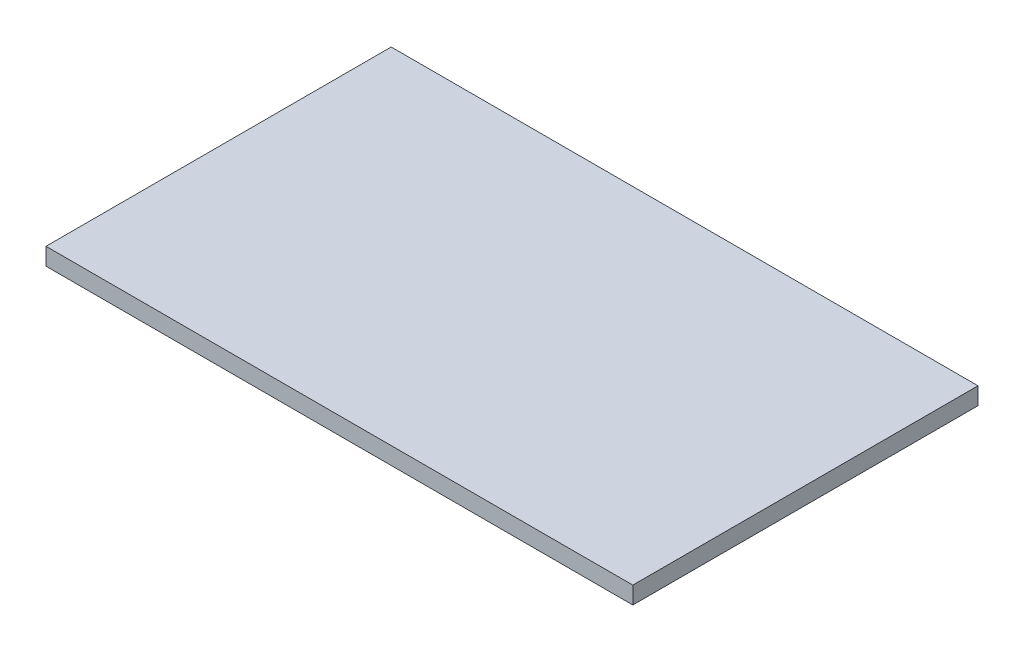
SolidWorks part; units mm, degrees
ref_plane "Front Plane" through (0, 0, 0) normal (0, 0, 1) x (1, 0, 0)
ref_plane "Top Plane" through (0, 0, 0) normal (0, 1, 0) x (1, 0, 0)
ref_plane "Right Plane" through (0, 0, 0) normal (1, 0, 0) x (0, 0, -1)
sketch "Sketch1" plane through (0, 0, 0) normal (0, 1, 0) x (1, 0, 0)
  line L0 (0, 0) -> (0, 254)
  line L1 (0, 254) -> (431.8, 254)
  line L2 (431.8, 254) -> (431.8, 0)
  line L3 (431.8, 0) -> (0, 0)
  dimension "D1" = 254
  dimension "D2" = 431.8
extrude "Boss-Extrude1" add sketch "Sketch1" along normal blind 12.7 contours L3 L0 L1 L2
sketch "Sketch2" plane through (0, 12.7, 0) normal (0, 1, 0) x (1, 0, 0)
  line L0 (0, 228.6) -> (431.8, 228.6)
  line L1 (0, 0) -> (0, 254) construction
  line L2 (431.8, 254) -> (431.8, 0) construction
  line L3 (0, 254) -> (431.8, 254) construction
  line L4 (0, 203.2) -> (431.8, 203.2)
  line L5 (0, 177.8) -> (431.8, 177.8)
  line L6 (0, 152.4) -> (431.8, 152.4)
  line L7 (0, 127) -> (431.8, 127)
  line L8 (0, 101.6) -> (431.8, 101.6)
  line L9 (0, 76.2) -> (431.8, 76.2)
  line L10 (0, 50.8) -> (431.8, 50.8)
  line L11 (0, 25.4) -> (431.8, 25.4)
  line L12 (50.8, 228.6) -> (50.8, 254)
  line L13 (101.6, 228.6) -> (101.6, 254)
  line L14 (152.4, 228.6) -> (152.4, 254)
  line L15 (203.2, 228.6) -> (203.2, 254)
  line L16 (254, 228.6) -> (254, 254)
  line L17 (304.8, 228.6) -> (304.8, 254)
  line L18 (355.6, 228.6) -> (355.6, 254)
  line L19 (406.4, 228.6) -> (406.4, 254)
  line L20 (25.4, 228.6) -> (25.4, 203.2)
  line L21 (76.2, 228.6) -> (76.2, 203.2)
  line L22 (127, 228.6) -> (127, 203.2)
  line L23 (177.8, 228.6) -> (177.8, 203.2)
  line L24 (228.6, 228.6) -> (228.6, 203.2)
  line L25 (279.4, 228.6) -> (279.4, 203.2)
  line L26 (330.2, 228.6) -> (330.2, 203.2)
  line L27 (381, 228.6) -> (381, 203.2)
  line L28 (50.8, 177.8) -> (50.8, 203.2)
  line L29 (101.6, 177.8) -> (101.6, 203.2)
  line L30 (152.4, 177.8) -> (152.4, 203.2)
  line L31 (203.2, 177.8) -> (203.2, 203.2)
  line L32 (254, 177.8) -> (254, 203.2)
  line L33 (304.8, 177.8) -> (304.8, 203.2)
  line L34 (355.6, 177.8) -> (355.6, 203.2)
  line L35 (406.4, 177.8) -> (406.4, 203.2)
  line L36 (50.8, 127) -> (50.8, 152.4)
  line L37 (101.6, 127) -> (101.6, 152.4)
  line L38 (152.4, 127) -> (152.4, 152.4)
  line L39 (203.2, 127) -> (203.2, 152.4)
  line L40 (254, 127) -> (254, 152.4)
  line L41 (304.8, 127) -> (304.8, 152.4)
  line L42 (355.6, 127) -> (355.6, 152.4)
  line L43 (406.4, 127) -> (406.4, 152.4)
  line L44 (50.8, 76.2) -> (50.8, 101.6)
  line L45 (101.6, 76.2) -> (101.6, 101.6)
  line L46 (152.4, 76.2) -> (152.4, 101.6)
  line L47 (203.2, 76.2) -> (203.2, 101.6)
  line L48 (254, 76.2) -> (254, 101.6)
  line L49 (304.8, 76.2) -> (304.8, 101.6)
  line L50 (355.6, 76.2) -> (355.6, 101.6)
  line L51 (406.4, 76.2) -> (406.4, 101.6)
  line L52 (50.8, 25.4) -> (50.8, 50.8)
  line L53 (101.6, 25.4) -> (101.6, 50.8)
  line L54 (152.4, 25.4) -> (152.4, 50.8)
  line L55 (203.2, 25.4) -> (203.2, 50.8)
  line L56 (254, 25.4) -> (254, 50.8)
  line L57 (304.8, 25.4) -> (304.8, 50.8)
  line L58 (355.6, 25.4) -> (355.6, 50.8)
  line L59 (406.4, 25.4) -> (406.4, 50.8)
  line L60 (25.4, 177.8) -> (25.4, 152.4)
  line L61 (76.2, 177.8) -> (76.2, 152.4)
  line L62 (127, 177.8) -> (127, 152.4)
  line L63 (177.8, 177.8) -> (177.8, 152.4)
  line L64 (228.6, 177.8) -> (228.6, 152.4)
  line L65 (279.4, 177.8) -> (279.4, 152.4)
  line L66 (330.2, 177.8) -> (330.2, 152.4)
  line L67 (381, 177.8) -> (381, 152.4)
  line L68 (25.4, 127) -> (25.4, 101.6)
  line L69 (76.2, 127) -> (76.2, 101.6)
  line L70 (127, 127) -> (127, 101.6)
  line L71 (177.8, 127) -> (177.8, 101.6)
  line L72 (228.6, 127) -> (228.6, 101.6)
  line L73 (279.4, 127) -> (279.4, 101.6)
  line L74 (330.2, 127) -> (330.2, 101.6)
  line L75 (381, 127) -> (381, 101.6)
  line L76 (25.4, 76.2) -> (25.4, 50.8)
  line L77 (76.2, 76.2) -> (76.2, 50.8)
  line L78 (127, 76.2) -> (127, 50.8)
  line L79 (177.8, 76.2) -> (177.8, 50.8)
  line L80 (228.6, 76.2) -> (228.6, 50.8)
  line L81 (279.4, 76.2) -> (279.4, 50.8)
  line L82 (330.2, 76.2) -> (330.2, 50.8)
  line L83 (381, 76.2) -> (381, 50.8)
  line L84 (25.4, 25.4) -> (25.4, 0)
  line L85 (76.2, 25.4) -> (76.2, 0)
  line L86 (127, 25.4) -> (127, 0)
  line L87 (177.8, 25.4) -> (177.8, 0)
  line L88 (228.6, 25.4) -> (228.6, 0)
  line L89 (279.4, 25.4) -> (279.4, 0)
  line L90 (330.2, 25.4) -> (330.2, 0)
  line L91 (381, 25.4) -> (381, 0)
  point P40 (406.4, 241.3)
  point P57 (381, 215.9)
  dimension "D1" = 25.4
  dimension "D2" = 25.4
  dimension "D3" = 25.4
  dimension "D4" = 25.4
  dimension "D5" = 25.4
  dimension "D6" = 25.4
  dimension "D7" = 25.4
  dimension "D8" = 25.4
  dimension "D9" = 50.8
  dimension "D10" = 50.8
  dimension "D11" = 50.8
  dimension "D12" = 50.8
  dimension "D13" = 50.8
  dimension "D14" = 50.8
  dimension "D15" = 50.8
  dimension "D16" = 50.8
  dimension "D17" = 25.4
  dimension "D18" = 50.8
  dimension "D19" = 50.8
  dimension "D20" = 50.8
  dimension "D21" = 50.8
  dimension "D22" = 50.8
  dimension "D23" = 50.8
  dimension "D24" = 50.8
  dimension "D25" = 5
  dimension "D26" = 5
